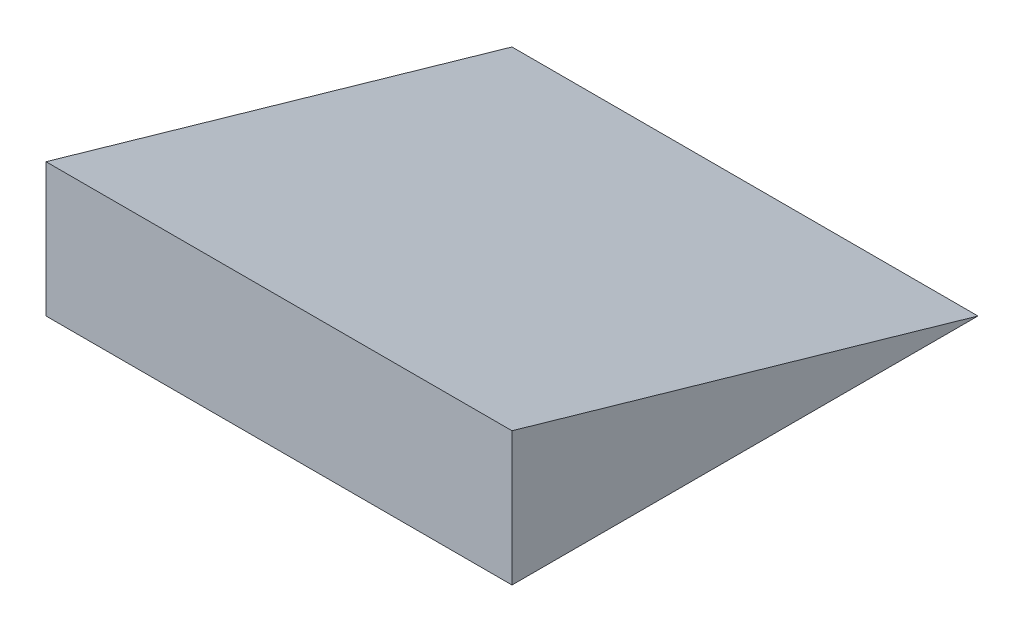
SolidWorks part; units mm, degrees
ref_plane "Front Plane" through (0, 0, 0) normal (0, 0, 1) x (1, 0, 0)
ref_plane "Top Plane" through (0, 0, 0) normal (0, 1, 0) x (1, 0, 0)
ref_plane "Right Plane" through (0, 0, 0) normal (1, 0, 0) x (0, 0, -1)
sketch "Sketch2" plane through (0, 0, 0) normal (1, 0, 0) x (0, 0, -1)
  line L0 (0, 0) -> (100, 0)
  line L1 (100, 0) -> (0, 28.6745)
  line L2 (0, 28.6745) -> (0, 0)
  dimension "D1" = 16
  dimension "D2" = 100
extrude "Boss-Extrude1" add sketch "Sketch2" along normal blind 100
